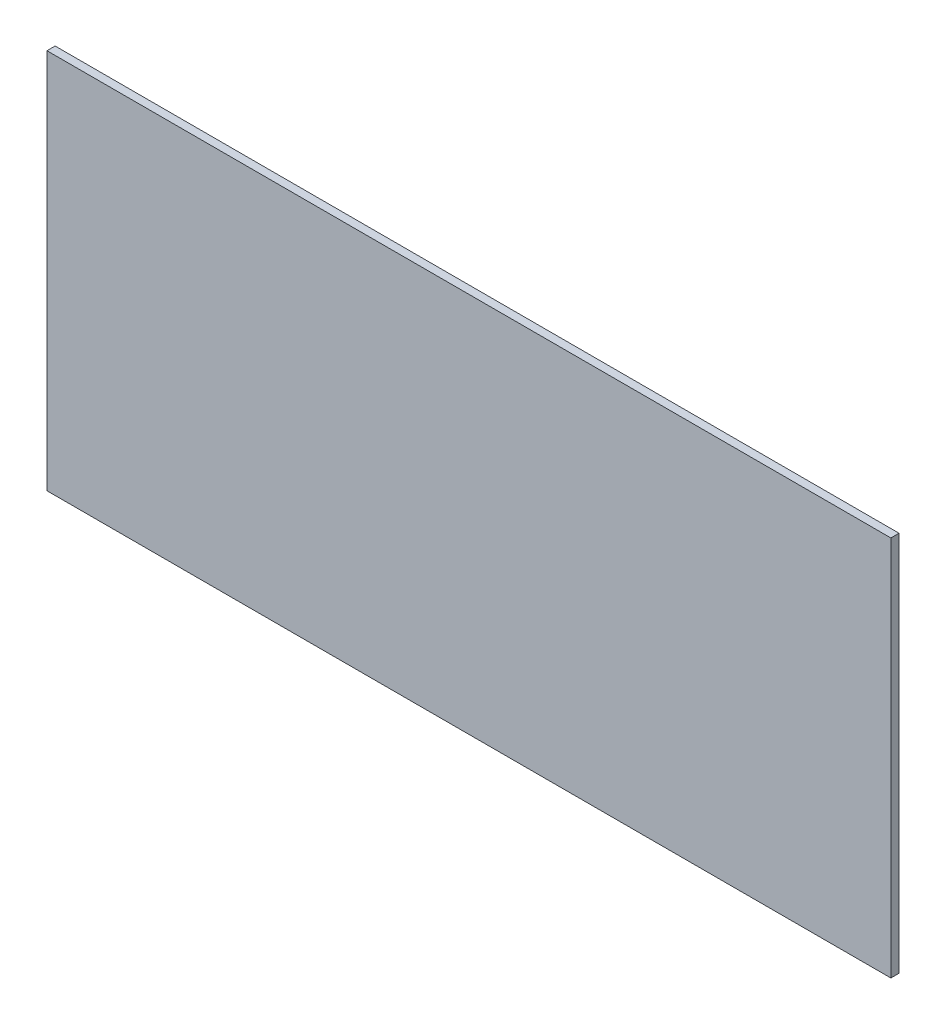
SolidWorks part; units mm, degrees
ref_plane "Front" through (0, 0, 0) normal (0, 0, 1) x (1, 0, 0)
ref_plane "Top" through (0, 0, 0) normal (0, 1, 0) x (1, 0, 0)
ref_plane "Right" through (0, 0, 0) normal (1, 0, 0) x (0, 0, -1)
sketch "Skizze1" plane through (0, 0, 0) normal (0, 0, 1) x (1, 0, 0)
  line L1 (-155, -70) -> (155, -70)
  line L2 (-155, -70) -> (-155, 70)
  line L3 (-155, 70) -> (155, 70)
  line L4 (155, -70) -> (155, 70)
  line L5 (-155, -70) -> (155, 70) construction
  line L6 (-155, 70) -> (155, -70) construction
  point P0 (0, 0)
  dimension "D1" = 310
  dimension "D2" = 140
extrude "Aufsatz-Linear austragen1" add sketch "Skizze1" along normal blind 3
